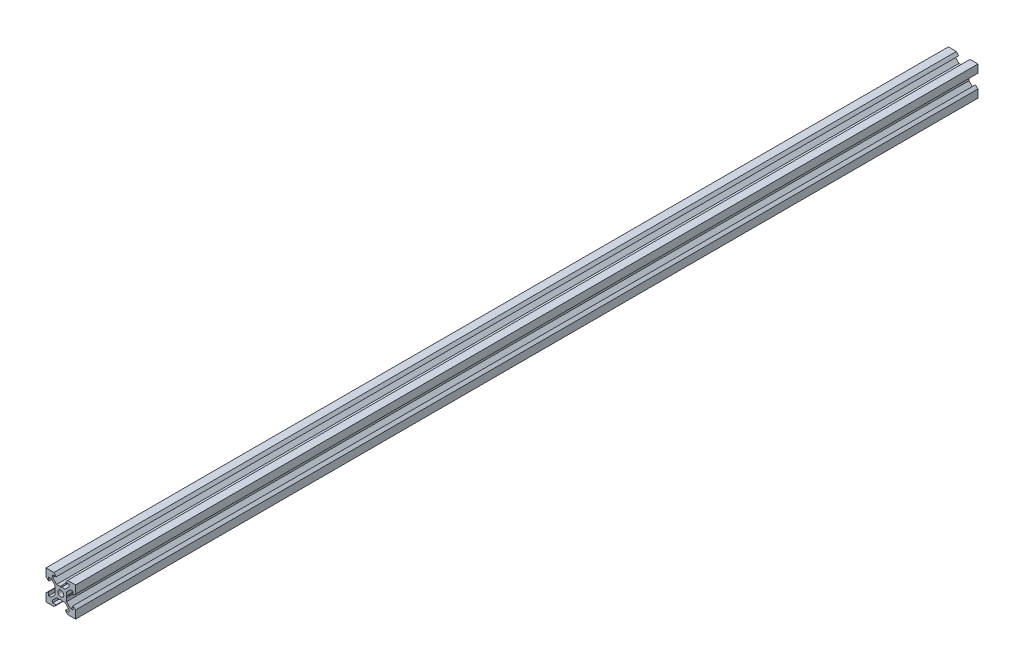
SolidWorks part; units mm, degrees
material "1060 Alloy"
ref_plane "Front Plane" through (0, 0, 0) normal (0, 0, 1) x (1, 0, 0)
ref_plane "Top Plane" through (0, 0, 0) normal (0, 1, 0) x (1, 0, 0)
ref_plane "Right Plane" through (0, 0, 0) normal (1, 0, 0) x (0, 0, -1)
sketch "Sketch1" plane through (0, 0, 0) normal (0, 0, 1) x (1, 0, 0)
  line L0 (10, 10) -> (4.6104, 10) construction
  line L1 (10, 10) -> (10, 4.6104) construction
  line L2 (10, -10) -> (10, -4.6104) construction
  line L3 (10, -10) -> (4.6104, -10) construction
  line L4 (10, 10) -> (10, 4.6104)
  line L5 (6.5607, 5.5) -> (8.2, 5.5)
  line L6 (5.5, 8.2) -> (5.5, 6.5607)
  line L7 (10, 10) -> (4.6104, 10)
  line L8 (10, 10) -> (10, 4.6104)
  line L9 (6.5607, 5.5) -> (3.9, 2.8393)
  line L10 (5.5, 6.5607) -> (2.8393, 3.9)
  line L11 (10, 4.6104) -> (8.2, 3.1)
  line L12 (4.6104, 10) -> (3.1, 8.2)
  line L13 (8.2, 3.1) -> (8.2, 5.5)
  line L14 (3.1, 8.2) -> (5.5, 8.2)
  line L15 (-6.5607, 5.5) -> (-8.2, 5.5)
  line L16 (6.5607, -5.5) -> (8.2, -5.5)
  line L17 (3.1, -8.2) -> (5.5, -8.2)
  line L18 (8.2, -3.1) -> (8.2, -5.5)
  line L19 (4.6104, -10) -> (3.1, -8.2)
  line L20 (10, -4.6104) -> (8.2, -3.1)
  line L21 (0.5196, -3.9) -> (0, -3.6)
  line L22 (0.5196, 3.9) -> (0, 3.6)
  line L23 (3.6, 0) -> (3.9, -0.5196)
  line L24 (3.9, 0.5196) -> (3.6, 0)
  line L25 (3.9, 0.5196) -> (3.9, 2.8393)
  line L26 (2.8393, 3.9) -> (0.5196, 3.9)
  line L27 (3.9, -2.8393) -> (3.9, -0.5196)
  line L28 (2.8393, -3.9) -> (0.5196, -3.9)
  line L29 (5.5, -6.5607) -> (2.8393, -3.9)
  line L30 (6.5607, -5.5) -> (3.9, -2.8393)
  line L31 (10, -10) -> (10, -4.6104)
  line L32 (10, -10) -> (4.6104, -10)
  line L33 (5.5, -8.2) -> (5.5, -6.5607)
  line L34 (-6.5607, -5.5) -> (-8.2, -5.5)
  line L35 (10, -10) -> (10, -4.6104)
  line L36 (0, 0) -> (0, 8.2) construction
  line L37 (-10, -10) -> (-4.6104, -10) construction
  line L38 (-10, -10) -> (-10, -4.6104) construction
  line L39 (-10, 10) -> (-10, 4.6104) construction
  line L40 (-10, 10) -> (-4.6104, 10) construction
  line L41 (-10, -10) -> (-10, -4.6104)
  line L43 (-5.5, -8.2) -> (-5.5, -6.5607)
  line L44 (-10, -10) -> (-4.6104, -10)
  line L45 (-10, -10) -> (-10, -4.6104)
  line L46 (-6.5607, -5.5) -> (-3.9, -2.8393)
  line L47 (-5.5, -6.5607) -> (-2.8393, -3.9)
  line L48 (-2.8393, -3.9) -> (-0.5196, -3.9)
  line L49 (-3.9, -2.8393) -> (-3.9, -0.5196)
  line L50 (-2.8393, 3.9) -> (-0.5196, 3.9)
  line L51 (-3.9, 0.5196) -> (-3.9, 2.8393)
  line L52 (-3.9, 0.5196) -> (-3.6, 0)
  line L53 (-3.6, 0) -> (-3.9, -0.5196)
  line L54 (-0.5196, 3.9) -> (0, 3.6)
  line L55 (-0.5196, -3.9) -> (0, -3.6)
  line L56 (-10, -4.6104) -> (-8.2, -3.1)
  line L57 (-4.6104, -10) -> (-3.1, -8.2)
  line L58 (-8.2, -3.1) -> (-8.2, -5.5)
  line L59 (-3.1, -8.2) -> (-5.5, -8.2)
  line L60 (-10, -10) -> (10, -10) construction
  line L61 (-10, -10) -> (-10, 10) construction
  line L62 (-3.1, 8.2) -> (-5.5, 8.2)
  line L63 (-8.2, 3.1) -> (-8.2, 5.5)
  line L64 (-4.6104, 10) -> (-3.1, 8.2)
  line L65 (-10, 4.6104) -> (-8.2, 3.1)
  line L66 (-5.5, 6.5607) -> (-2.8393, 3.9)
  line L67 (-6.5607, 5.5) -> (-3.9, 2.8393)
  line L68 (-10, 10) -> (-10, 4.6104)
  line L69 (-10, 10) -> (-4.6104, 10)
  line L70 (-5.5, 8.2) -> (-5.5, 6.5607)
  line L71 (-10, 10) -> (10, 10) construction
  line L72 (-10, 10) -> (-10, 4.6104)
  line L73 (10, -10) -> (10, 10) construction
  line L74 (-10, -10) -> (10, 10) construction
  line L75 (-10, 10) -> (10, -10) construction
  circle A0 centre (0, 0) radius 2
  dimension "D7" = 4
  dimension "D1" = 20
  dimension "D2" = 5.3896
  dimension "D3" = 4.5
  dimension "D4" = 50
  dimension "D5" = 1.8
  dimension "D6" = 1.5104
  dimension "D8" = 5.5
  dimension "D9" = 120
  dimension "D10" = 0.3
  dimension "D11" = 2.3197
  dimension "D12" = 7.8
  dimension "D13" = 7.8
  dimension "D14" = 1.5
  dimension "D15" = 2.6607
extrude "Boss-Extrude1" add sketch "Sketch1" along normal mid plane 609.3 contours L70 L62 L64 L69 L68 L65 L63 L15 L67 L51 L52 L53 L49 L46 L34 L58 L56 L41 L44 L57 L59 L43 L47 L48 L55 L21 L28 L29 L33 L17 L19 L32 L31 L20 L18 L16 L30 L27 L23 L24 L25 L9 L5 L13 L11 L4 L7 L12 L14 L6 L10
